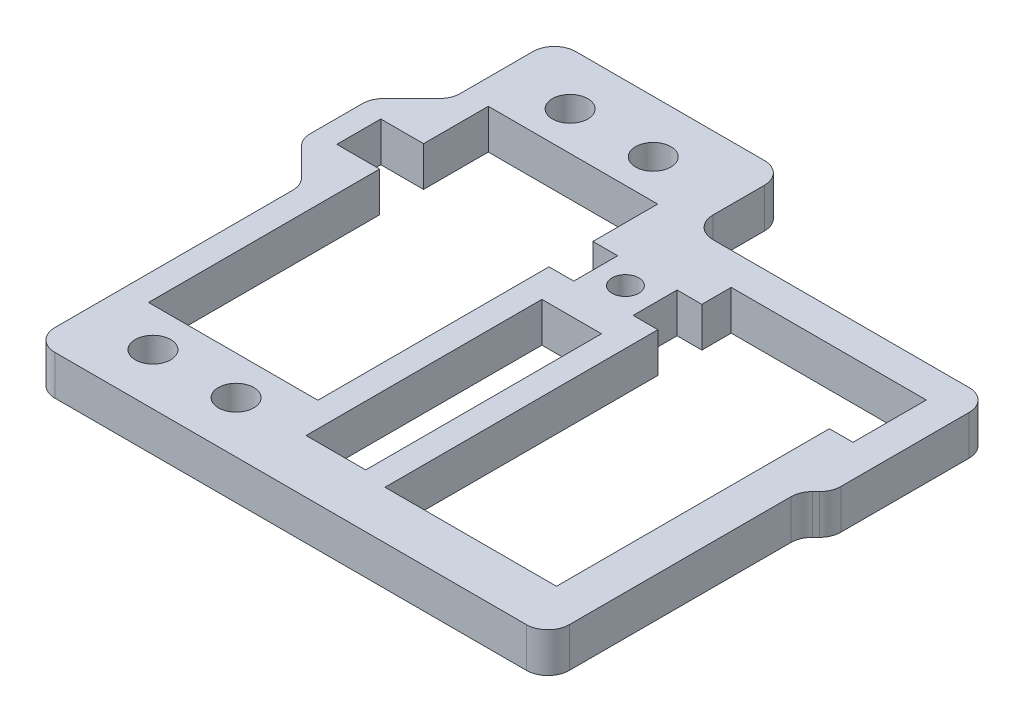
SolidWorks part; units mm, degrees
material "Custom Plastic"
ref_plane "Front Plane" through (0, 0, 0) normal (0, 0, 1) x (1, 0, 0)
ref_plane "Top Plane" through (0, 0, 0) normal (0, 1, 0) x (1, 0, 0)
ref_plane "Right Plane" through (0, 0, 0) normal (1, 0, 0) x (0, 0, -1)
sketch "Sketch1" plane through (0, 0, 0) normal (0, 1, 0) x (1, 0, 0)
  line L0 (0, 0) -> (30.48, 0)
  line L1 (30.48, 0) -> (30.48, 29.845)
  line L2 (30.48, 29.845) -> (32.385, 31.75)
  line L3 (32.385, 31.75) -> (32.385, 50.546)
  line L4 (32.385, 50.546) -> (-3.048, 50.546)
  line L5 (-3.048, 50.546) -> (-3.048, 61.722)
  line L6 (-3.048, 61.722) -> (-30.48, 61.722)
  line L7 (-30.48, 61.722) -> (-30.48, 49.5427)
  line L8 (-30.48, 49.5427) -> (-35.2425, 44.7802)
  line L9 (-35.2425, 44.7802) -> (-35.2425, 36.5252)
  line L10 (-35.2425, 36.5252) -> (-30.48, 31.7627)
  line L11 (-30.48, 31.7627) -> (-30.48, 0)
  line L12 (-30.48, 0) -> (0, 0)
  line L13 (5.461, 5.715) -> (25.781, 5.715)
  line L14 (25.781, 5.715) -> (25.781, 38.0492)
  line L15 (25.781, 38.0492) -> (28.575, 38.0492)
  line L16 (28.575, 38.0492) -> (28.575, 46.736)
  line L17 (28.575, 46.736) -> (5.461, 46.736)
  line L18 (5.461, 46.736) -> (5.461, 43.2562)
  line L19 (5.461, 43.2562) -> (2.5273, 43.2562)
  line L20 (2.5273, 43.2562) -> (2.5273, 38.0492)
  line L21 (2.5273, 38.0492) -> (5.461, 38.0492)
  line L22 (5.461, 38.0492) -> (5.461, 5.715)
  line L23 (-27.5082, 10.668) -> (-7.4422, 10.668)
  line L24 (2.54, 34.29) -> (-4.5212, 34.29)
  line L25 (2.54, 34.29) -> (2.54, 6.35)
  line L26 (2.54, 6.35) -> (-4.5212, 6.35)
  line L27 (-4.5212, 34.29) -> (-4.5212, 6.35)
  line L28 (-7.4422, 10.668) -> (-7.4422, 38.0492)
  line L29 (-7.4422, 38.0492) -> (-4.5085, 38.0492)
  line L30 (-4.5085, 38.0492) -> (-4.5085, 43.2562)
  line L31 (-4.5085, 43.2562) -> (-7.4422, 43.2562)
  line L32 (-7.4422, 43.2562) -> (-7.4422, 50.927)
  line L33 (-7.4422, 50.927) -> (-27.5082, 50.927)
  line L34 (-27.5082, 50.927) -> (-27.5082, 43.2562)
  line L35 (-27.5082, 43.2562) -> (-32.5755, 43.2562)
  line L36 (-32.5755, 43.2562) -> (-32.5755, 38.0492)
  line L37 (-32.5755, 38.0492) -> (-27.5082, 38.0492)
  line L38 (-27.5082, 38.0492) -> (-27.5082, 10.668)
  line L39 (-4.5085, 40.6527) -> (2.5273, 40.6527) construction
  line L40 (-32.5755, 40.6527) -> (-35.2425, 40.6527) construction
  line L41 (-27.5082, 50.927) -> (-7.4422, 10.668) construction
  line L42 (-27.5082, 10.668) -> (-7.4422, 50.927) construction
  line L44 (-22.4003, 6.0858) -> (-12.5501, 6.0858) construction
  line L45 (-22.4003, 6.0858) -> (-22.4003, 55.5092) construction
  line L46 (-22.4003, 55.5092) -> (-12.5501, 55.5092) construction
  line L47 (-12.5501, 6.0858) -> (-12.5501, 55.5092) construction
  line L48 (-22.4003, 6.0858) -> (-12.5501, 55.5092) construction
  line L49 (-22.4003, 55.5092) -> (-12.5501, 6.0858) construction
  circle A0 centre (-0.9906, 40.6527) radius 1.5875
  circle A1 centre (-12.5501, 55.5092) radius 2.0955
  circle A2 centre (-22.4003, 55.5092) radius 2.0955
  circle A3 centre (-12.5501, 6.0858) radius 2.0955
  circle A4 centre (-22.4003, 6.0858) radius 2.0955
  point P42 (-17.4752, 30.7975)
  dimension "D18" = 3.175
  dimension "D31" = 4.191
  dimension "D1" = 60.96
  dimension "D2" = 50.546
  dimension "D3" = 61.722
  dimension "D4" = 5.715
  dimension "D5" = 4.699
  dimension "D6" = 3.81
  dimension "D7" = 3.81
  dimension "D8" = 20.32
  dimension "D9" = 45
  dimension "D10" = 5.207
  dimension "D11" = 7.2898
  dimension "D12" = 6.35
  dimension "D13" = 7.0612
  dimension "D14" = 2.921
  dimension "D15" = 2.921
  dimension "D16" = 27.94
  dimension "D17" = 7.0358
  dimension "D19" = 20.066
  dimension "D20" = 10.668
  dimension "D21" = 28.067
  dimension "D22" = 2.667
  dimension "D23" = 45
  dimension "D24" = 40.259
  dimension "D25" = 27.432
  dimension "D26" = 8.255
  dimension "D27" = 23.114
  dimension "D28" = 20.701
  dimension "D29" = 9.8501
  dimension "D30" = 49.4233
extrude "Boss-Extrude1" add sketch "Sketch1" along normal blind 4.699 contours L37 L38 L23 L28 L29 L30 L31 L32 L33 L34 L35 L36 | A0 | L24 L27 L26 L25 | L21 L22 L13 L14 L15 L16 L17 L18 L19 L20 | A2 | A1 | A3 | A4 | L6 L7 L8 L9 L10 L11 L12 L0 L1 L2 L3 L4 L5
fillet "Fillet1" radius 2.54 12 edges at (-30.48, 2.3495, -49.5427) (-35.2425, 2.3495, -44.7802) (-35.2425, 2.3495, -36.5252) (-30.48, 2.3495, -31.7627) (-30.48, 2.3495, 0) (30.48, 2.3495, 0) (30.48, 2.3495, -29.845) (32.385, 2.3495, -31.75) (32.385, 2.3495, -50.546) (-3.048, 2.3495, -50.546) (-30.48, 2.3495, -61.722) (-3.048, 2.3495, -61.722)
